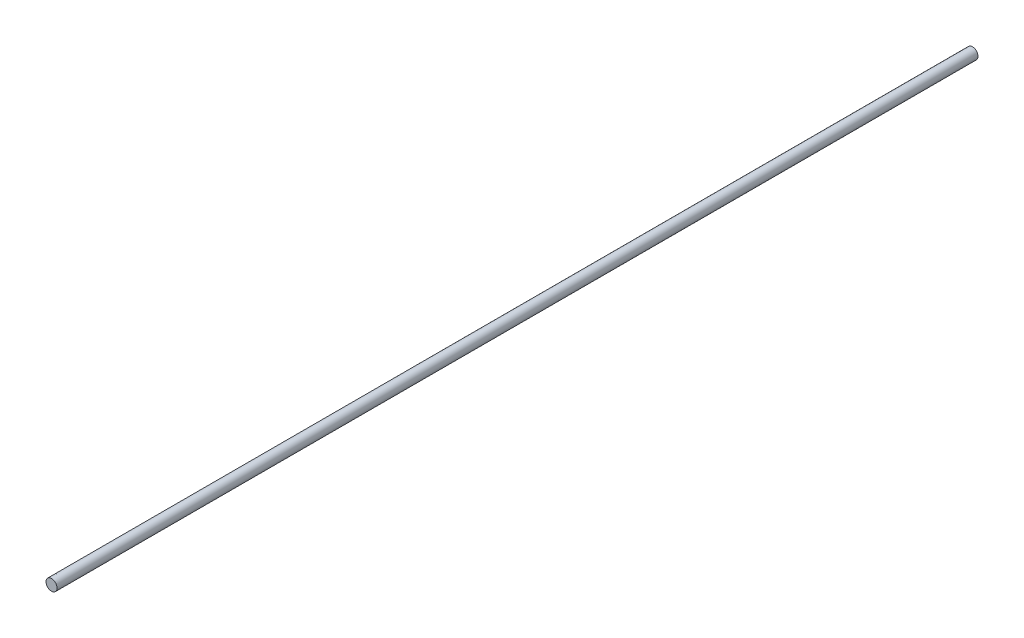
SolidWorks part; units mm, degrees
ref_plane "Plan de face" through (0, 0, 0) normal (0, 0, 1) x (1, 0, 0)
ref_plane "Plan de dessus" through (0, 0, 0) normal (0, 1, 0) x (1, 0, 0)
ref_plane "Plan de droite" through (0, 0, 0) normal (1, 0, 0) x (0, 0, -1)
sketch "Esquisse1" plane through (0, 0, 0) normal (0, 0, 1) x (1, 0, 0)
  circle A0 centre (0, 0) radius 3
  dimension "D1" = 6
extrude "Boss.-Extru.1" add sketch "Esquisse1" along normal blind 500
